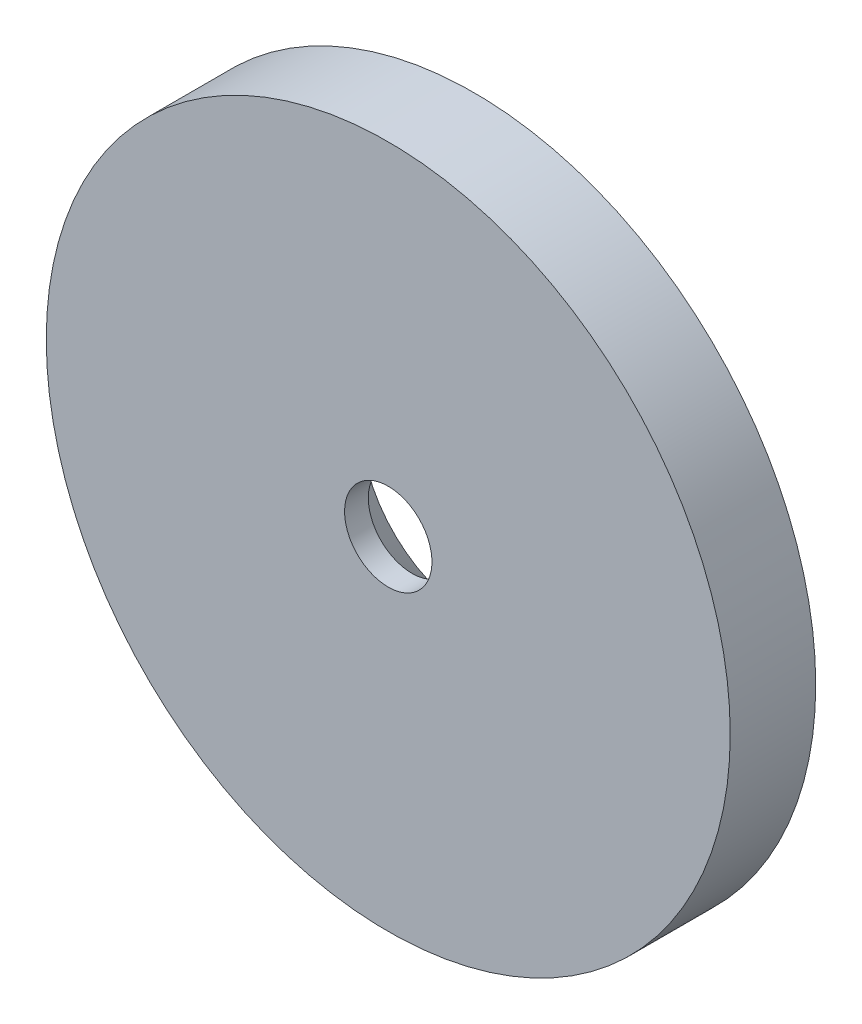
SolidWorks part; units mm, degrees
ref_plane "Front Plane" through (0, 0, 0) normal (0, 0, 1) x (1, 0, 0)
ref_plane "Top Plane" through (0, 0, 0) normal (0, 1, 0) x (1, 0, 0)
ref_plane "Right Plane" through (0, 0, 0) normal (1, 0, 0) x (0, 0, -1)
sketch "Sketch1" plane through (0, 0, 0) normal (0, 0, 1) x (1, 0, 0)
  circle A0 centre (0, 0) radius 9.144
extrude "Boss-Extrude1" add sketch "Sketch1" along normal blind 2.286 contours A0
hole_wizard "CBORE for #1 Binding Head Machine Screw2" positions "Sketch6" profile "Sketch7" counterbore size "#1" standard "ANSI Inch" end condition through all
sketch "Sketch6" plane through (0, 0, 0) normal (0, 0, -1) x (-1, 0, 0)
  point P0 (0, 0)
sketch "Sketch7" plane through (0, 0, 0) normal (1, 0, 0) x (0, 1, 0)
  line L0 (0, 0) -> (0, 2.286)
  line L1 (0, 2.286) -> (1.1684, 2.286)
  line L3 (1.1684, 2.286) -> (1.1684, 1.651)
  line L4 (1.651, 1.651) -> (1.1684, 1.651)
  line L5 (1.651, 1.651) -> (1.651, 1.3653)
  line L6 (1.651, 1.3653) -> (3.0162, 0)
  line L7 (3.0162, 0) -> (0, 0)
  line L8 (-1.651, 1.3652) -> (-3.0162, 0) construction
  line L11 (0, -6.35) -> (0, 107.95) construction
  dimension "Thru Hole Dia." = 2.3368
  dimension "Thru Hole Depth" = 2.286
  dimension "C'Bore Dia." = 3.302
  dimension "C'Bore Depth" = 1.651
  dimension "Near C'Sink Dia." = 6.0325
  dimension "Near C'Sink Angle" = 90
